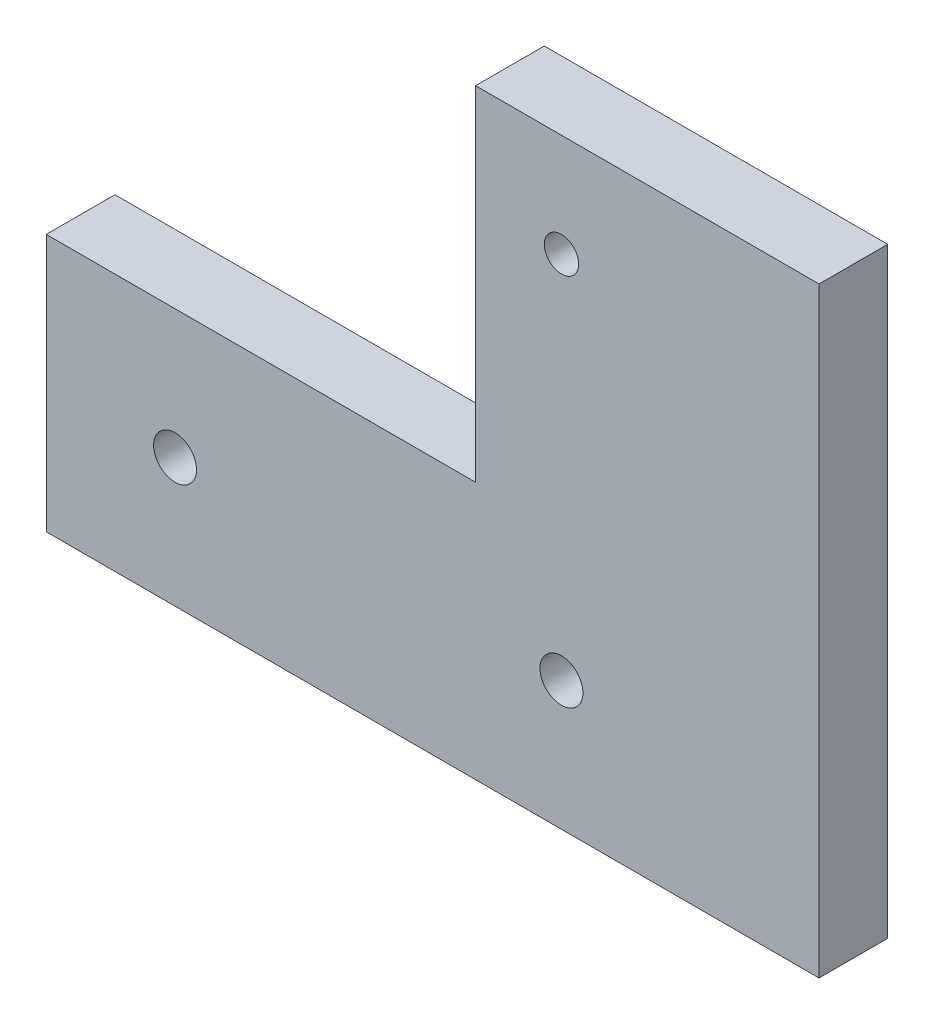
SolidWorks part; units mm, degrees
ref_plane "Front Plane" through (0, 0, 0) normal (0, 0, 1) x (1, 0, 0)
ref_plane "Top Plane" through (0, 0, 0) normal (0, 1, 0) x (1, 0, 0)
ref_plane "Right Plane" through (0, 0, 0) normal (1, 0, 0) x (0, 0, -1)
sketch "Sketch1" plane through (0, 0, 0) normal (0, 0, 1) x (1, 0, 0)
  line L0 (-50.7249, 17.2941) -> (-10.7249, 17.2941)
  line L1 (-10.7249, 17.2941) -> (-10.7249, -52.7059)
  line L2 (-10.7249, -52.7059) -> (-100.7249, -52.7059)
  line L3 (-100.7249, -52.7059) -> (-100.7249, -22.7059)
  line L4 (-100.7249, -22.7059) -> (-50.7249, -22.7059)
  line L5 (-50.7249, -22.7059) -> (-50.7249, 17.2941)
  circle A0 centre (-85.7249, -37.7059) radius 2.5
  circle A1 centre (-40.7249, -37.7059) radius 2.5
  dimension "D2" = 5
  dimension "D8" = 15
  dimension "D3" = 5
  dimension "D1" = 70
  dimension "D4" = 40
  dimension "D5" = 15
  dimension "D6" = 90
  dimension "D7" = 15
  dimension "D9" = 30
extrude "Boss-Extrude1" add sketch "Sketch1" along normal blind 8
sketch "Sketch2" plane through (0, 0, 0) normal (0, 0, -1) x (-1, 0, 0)
  line L0 (10.7249, -52.7059) -> (10.7249, 17.2941) construction
  line L1 (100.7249, -52.7059) -> (10.7249, -52.7059) construction
  circle A0 centre (40.7249, 5.2941) radius 7.5
  dimension "D2" = 15
  dimension "D1" = 30
  dimension "D3" = 58
extrude "Cut-Extrude1" cut sketch "Sketch2" against normal blind 5
sketch "Sketch3" plane through (0, 0, 5) normal (0, 0, -1) x (-1, 0, 0)
  circle A0 centre (40.7249, 5.2941) radius 2
  dimension "D1" = 4
extrude "Cut-Extrude2" cut sketch "Sketch3" against normal through all
